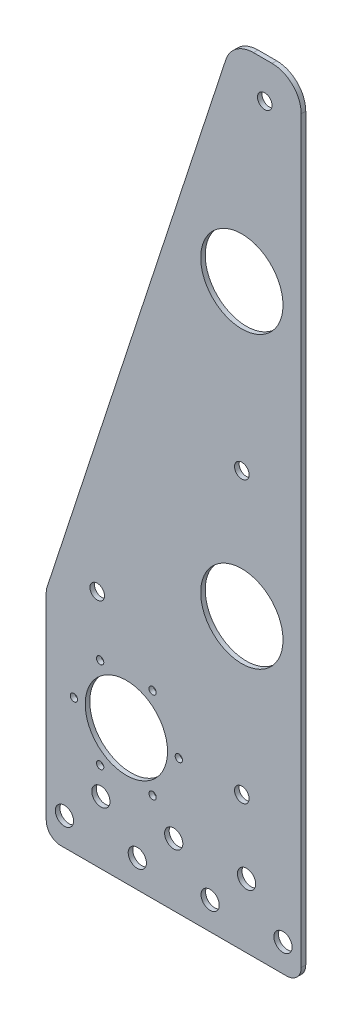
SolidWorks part; units mm, degrees
material "6061 Alloy"
ref_plane "Front Plane" through (0, 0, 0) normal (0, 0, 1) x (1, 0, 0)
ref_plane "Top Plane" through (0, 0, 0) normal (0, 1, 0) x (1, 0, 0)
ref_plane "Right Plane" through (0, 0, 0) normal (1, 0, 0) x (0, 0, -1)
sketch "Sketch1" plane through (0, 0, 0) normal (0, 0, 1) x (1, 0, 0)
  line L2 (88.9, 212.09) -> (88.9, 5.08)
  line L3 (83.82, 0) -> (5.08, 0)
  line L4 (78.74, 222.25) -> (55.6253, 222.25)
  line L5 (45.9692, 215.25) -> (0.252, 75.55)
  line L6 (0, 73.97) -> (0, 5.08)
  line L7 (6.35, 9.652) -> (31.75, 9.652) construction
  line L8 (27.94, 46.99) -> (27.94, 82.7405) construction
  line L9 (27.94, 46.99) -> (60.7143, 46.99) construction
  circle A0 centre (68.199, 201.93) radius 14.351
  circle A1 centre (68.199, 100.838) radius 14.351
  circle A2 centre (68.199, 144.78) radius 2.54
  circle A3 centre (68.199, 46.99) radius 2.54
  arc A4 (78.74, 222.25) -> (88.9, 212.09) centre (78.74, 212.09) cw
  arc A5 (0, 5.08) -> (5.08, 0) centre (5.08, 5.08) ccw
  arc A6 (88.9, 5.08) -> (83.82, 0) centre (83.82, 5.08) cw
  arc A7 (55.6253, 222.25) -> (45.9692, 215.25) centre (55.6253, 212.09) ccw
  arc A8 (0.252, 75.55) -> (0, 73.97) centre (5.08, 73.97) ccw
  circle A9 centre (27.94, 46.99) radius 14.351
  circle A17 centre (68.199, 201.93) radius 50.8 construction
  circle A18 centre (68.199, 100.838) radius 38.1 construction
  circle A19 centre (6.35, 9.652) radius 3.175
  circle A21 centre (31.75, 9.652) radius 3.175
  circle A22 centre (57.15, 9.652) radius 3.175
  circle A23 centre (82.55, 9.652) radius 3.175
  circle A29 centre (69.85, 22.352) radius 3.175
  circle A30 centre (44.45, 21.844) radius 3.175
  circle A31 centre (19.05, 21.844) radius 3.175
  circle A32 centre (46.228, 46.99) radius 1.27
  circle A38 centre (37.084, 31.1521) radius 1.27
  circle A39 centre (18.796, 31.1521) radius 1.27
  circle A40 centre (9.652, 46.99) radius 1.27
  circle A41 centre (18.796, 62.8279) radius 1.27
  circle A42 centre (37.084, 62.8279) radius 1.27
  point P17 (88.9, 222.25)
  point P20 (0, 0)
  point P23 (88.9, 0)
  point P25 (48.26, 222.25)
  point P26 (48.26, 222.25)
  point P43 (27.94, 46.99)
  point P69 (27.94, 46.99)
  dimension "D1" = 28.702
  dimension "D2" = 28.702
  dimension "D4" = 88.9
  dimension "D7" = 5.08
  dimension "D9" = 5.08
  dimension "D11" = 10.16
  dimension "D12" = 5.08
  dimension "D13" = 10.16
  dimension "D14" = 5.08
  dimension "D16" = 28.702
  dimension "D17" = 18.288
  dimension "D23" = 139.7
  dimension "D24" = 101.6
  dimension "D25" = 76.2
  dimension "D26" = 6.35
  dimension "D29" = 21.844
  dimension "D31" = 6.35
  dimension "D32" = 4
  dimension "D34" = 19.05
  dimension "D39" = 21.844
  dimension "D30" = 6.35
  dimension "D35" = 6.35
  dimension "D37" = 6.35
  dimension "D38" = 25.4
  dimension "D18" = 2.54
  dimension "D3" = 101.092
  dimension ".75" = 20.701
  dimension "D5" = 222.25
  dimension "D6" = 20.32
  dimension "D8" = 57.15
  dimension "D10" = 97.79
  dimension "D15" = 40.64
  dimension "D20" = 27.94
  dimension "D21" = 9.144
  dimension "D22" = 15.8379
  dimension "D27" = 9.652
  dimension "D28" = 25.4
  dimension "D33" = 12.7
  dimension "D36" = 25.4
  dimension "D19" = 6
extrude "Boss-Extrude1" add sketch "Sketch1" along normal blind 1.5875
sketch "Sketch2" plane through (0, 0, 1.5875) normal (0, 0, 1) x (1, 0, 0)
  line L0 (45.9692, 215.25) -> (62.5937, 266.05)
  line L1 (45.9692, 215.25) -> (0.252, 75.55) construction
  line L2 (72.2498, 273.05) -> (78.74, 273.05)
  line L3 (88.9, 262.89) -> (88.9, 212.09)
  line L4 (78.74, 222.25) -> (55.6253, 222.25) construction
  line L5 (45.9692, 215.25) -> (55.6253, 222.25)
  line L6 (55.6253, 222.25) -> (78.74, 222.25)
  line L7 (78.74, 222.25) -> (88.9, 212.09)
  line L8 (76.2, 156.304) -> (76.2, 48.354) construction
  line L9 (88.9, 5.08) -> (88.9, 212.09) construction
  arc A0 (78.74, 273.05) -> (88.9, 262.89) centre (78.74, 262.89) cw
  arc A1 (62.5937, 266.05) -> (72.2498, 273.05) centre (72.2498, 262.89) cw
  circle A2 centre (76.2, 260.35) radius 2.54
  point P19 (68.199, 144.78)
  dimension "D2" = 10.16
  dimension "D3" = 5.08
  dimension "D1" = 50.8
  dimension "D4" = 12.7
  dimension "D5" = 12.7
extrude "Boss-Extrude2" add sketch "Sketch2" against normal blind 1.5875 contours L2 A0 L3 L7 L6 L5 L0 A1
sketch "Sketch3" plane through (0, 0, 1.5875) normal (0, 0, 1) x (1, 0, 0)
  line L0 (68.199, 83.058) -> (-39.9215, 83.058) construction
  line L1 (17.78, 46.99) -> (17.78, -14.087) construction
  circle A1 centre (17.78, 83.058) radius 2.54
  point P0 (68.199, 100.838)
  point P2 (27.94, 46.99)
  dimension "D1" = 5.08
  dimension "D2" = 10.16
  dimension "D3" = 17.78
extrude "Cut-Extrude1" cut sketch "Sketch3" against normal through all contours A1
